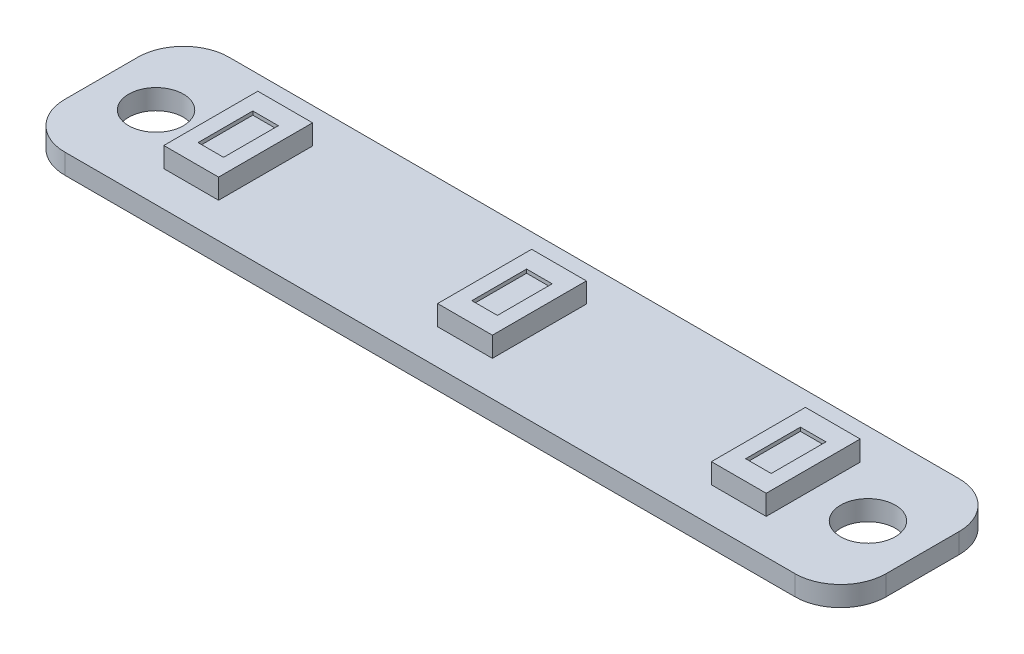
SolidWorks part; units mm, degrees
ref_plane "Front Plane" through (0, 0, 0) normal (0, 0, 1) x (1, 0, 0)
ref_plane "Top Plane" through (0, 0, 0) normal (0, 1, 0) x (1, 0, 0)
ref_plane "Right Plane" through (0, 0, 0) normal (1, 0, 0) x (0, 0, -1)
sketch "Sketch1" plane through (0, 0, 0) normal (0, 1, 0) x (1, 0, 0)
  line L0 (-22.5, 0) -> (22.5, 0) construction
  line L1 (-20, 4.5) -> (20, 4.5)
  line L2 (-22.5, 2) -> (-22.5, -2)
  line L3 (-20, -4.5) -> (20, -4.5)
  line L4 (22.5, 2) -> (22.5, -2)
  line L5 (-22.5, 4.5) -> (22.5, -4.5) construction
  line L6 (-22.5, -4.5) -> (22.5, 4.5) construction
  line L7 (0, -4.5) -> (0, 4.5) construction
  circle A0 centre (-19.5, 0) radius 1.5
  circle A1 centre (19.5, 0) radius 1.5
  arc A2 (20, 4.5) -> (22.5, 2) centre (20, 2) cw
  arc A3 (20, -4.5) -> (22.5, -2) centre (20, -2) ccw
  arc A4 (-22.5, -2) -> (-20, -4.5) centre (-20, -2) ccw
  arc A5 (-20, 4.5) -> (-22.5, 2) centre (-20, 2) ccw
  point P0 (0, 0)
  dimension "D4" = 3
  dimension "D5" = 2.5
  dimension "D1" = 45
  dimension "D2" = 9
  dimension "D3" = 39
extrude "Boss-Extrude1" add sketch "Sketch1" along normal blind 1.1
sketch "Sketch2" plane through (0, 1.1, 0) normal (0, 1, 0) x (1, 0, 0)
  line L0 (-22.5, 0) -> (22.5, 0) construction
  line L1 (-22.5, 2) -> (-22.5, -2) construction
  line L2 (22.5, -2) -> (22.5, 2) construction
  line L3 (0, 4.5) -> (0, -4.5) construction
  line L4 (20, 4.5) -> (-20, 4.5) construction
  line L5 (-20, -4.5) -> (20, -4.5) construction
  line L6 (13.5, 2.575) -> (13.5, -2.575)
  line L7 (-16.5, 2.575) -> (-13.5, 2.575)
  line L8 (-16.5, 2.575) -> (-16.5, -2.575)
  line L9 (-16.5, -2.575) -> (-13.5, -2.575)
  line L10 (-13.5, 2.575) -> (-13.5, -2.575)
  line L11 (-16.5, 2.575) -> (-13.5, -2.575) construction
  line L12 (-16.5, -2.575) -> (-13.5, 2.575) construction
  line L13 (-1.5, 2.575) -> (1.5, 2.575)
  line L14 (-1.5, 2.575) -> (-1.5, -2.575)
  line L15 (-1.5, -2.575) -> (1.5, -2.575)
  line L16 (1.5, 2.575) -> (1.5, -2.575)
  line L17 (-1.5, 2.575) -> (1.5, -2.575) construction
  line L18 (-1.5, -2.575) -> (1.5, 2.575) construction
  line L19 (16.5, -2.575) -> (13.5, -2.575)
  line L20 (16.5, 2.575) -> (16.5, -2.575)
  line L21 (16.5, 2.575) -> (13.5, 2.575)
  circle A0 centre (-19.5, 0) radius 1.5 construction
  point P12 (-15, 0)
  point P17 (0, 0)
  dimension "D1" = 3
  dimension "D2" = 5.15
  dimension "D3" = 4.5
extrude "Boss-Extrude2" add sketch "Sketch2" along normal blind 1.1
sketch "Sketch3" plane through (0, 2.2, 0) normal (0, 1, 0) x (1, 0, 0)
  line L0 (-16.5, 0) -> (16.5, 0) construction
  line L1 (-16.5, 2.575) -> (-16.5, -2.575) construction
  line L2 (16.5, -2.575) -> (16.5, 2.575) construction
  line L3 (0, 2.575) -> (0, -2.575) construction
  line L4 (1.5, 2.575) -> (-1.5, 2.575) construction
  line L5 (-1.5, -2.575) -> (1.5, -2.575) construction
  line L6 (-15, 2.575) -> (-15, -2.575) construction
  line L7 (-13.5, 2.575) -> (-16.5, 2.575) construction
  line L8 (-16.5, -2.575) -> (-13.5, -2.575) construction
  line L9 (15, 2.575) -> (15, -2.575) construction
  line L10 (16.5, 2.575) -> (13.5, 2.575) construction
  line L11 (13.5, -2.575) -> (16.5, -2.575) construction
  line L12 (15.7, -1.5) -> (14.3, -1.5)
  line L13 (-15.7, 1.5) -> (-14.3, 1.5)
  line L14 (-15.7, 1.5) -> (-15.7, -1.5)
  line L15 (-15.7, -1.5) -> (-14.3, -1.5)
  line L16 (-14.3, 1.5) -> (-14.3, -1.5)
  line L17 (-15.7, 1.5) -> (-14.3, -1.5) construction
  line L18 (-15.7, -1.5) -> (-14.3, 1.5) construction
  line L19 (-0.7, 1.5) -> (0.7, 1.5)
  line L20 (-0.7, 1.5) -> (-0.7, -1.5)
  line L21 (-0.7, -1.5) -> (0.7, -1.5)
  line L22 (0.7, 1.5) -> (0.7, -1.5)
  line L23 (-0.7, 1.5) -> (0.7, -1.5) construction
  line L24 (-0.7, -1.5) -> (0.7, 1.5) construction
  line L25 (14.3, 1.5) -> (14.3, -1.5)
  line L26 (15.7, 1.5) -> (14.3, 1.5)
  line L27 (15.7, 1.5) -> (15.7, -1.5)
  point P24 (-15, 0)
  point P29 (0, 0)
  dimension "D1" = 1.4
  dimension "D2" = 3
extrude "Cut-Extrude1" cut sketch "Sketch3" against normal blind 0.2
